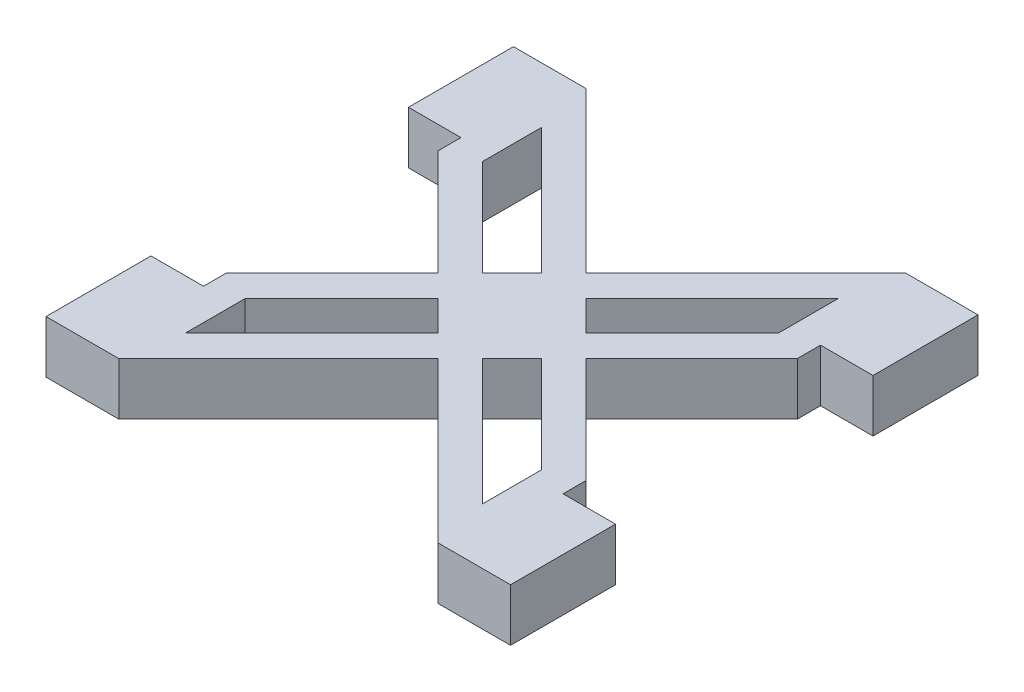
SolidWorks part; units mm, degrees
ref_plane "Front Plane" through (0, 0, 0) normal (0, 0, 1) x (1, 0, 0)
ref_plane "Top Plane" through (0, 0, 0) normal (0, 1, 0) x (1, 0, 0)
ref_plane "Right Plane" through (0, 0, 0) normal (1, 0, 0) x (0, 0, -1)
sketch "Sketch1" plane through (0, 0, 0) normal (0, 1, 0) x (1, 0, 0)
  line L0 (8.9803, 0) -> (-8.9803, 0) construction
  line L1 (6.2862, 2.6941) -> (2.6941, 6.2862)
  line L2 (4.4901, 4.4901) -> (-20.373, 29.3533) construction
  line L3 (-28.0924, 15.5702) -> (-28.0924, 28.2702)
  line L4 (0, 0) -> (24.8632, 24.8632) construction
  line L5 (21.7424, 15.5702) -> (21.7424, 12.7621)
  line L6 (28.0924, 28.2702) -> (19.2899, 28.2702)
  line L7 (0, 0) -> (-24.8632, 24.8632) construction
  line L8 (28.0924, 15.5702) -> (21.7424, 15.5702)
  line L9 (-8.9803, 0) -> (-21.7424, 12.7621)
  line L10 (2.6941, -6.2862) -> (6.2862, -2.6941)
  line L11 (-4.4901, -4.4901) -> (-29.3533, 20.373) construction
  line L12 (28.0924, 15.5702) -> (28.0924, 28.2702)
  line L13 (-6.2862, 2.6941) -> (-2.6941, 6.2862)
  line L14 (0, -27.6063) -> (0, 27.6063) construction
  line L15 (0, 0) -> (-24.8632, -24.8632) construction
  line L16 (0, 0) -> (24.8632, -24.8632) construction
  line L17 (-21.7424, -15.5702) -> (-21.7424, -12.7621)
  line L18 (-28.0924, -28.2702) -> (-19.2899, -28.2702)
  line L19 (-28.0924, -15.5702) -> (-21.7424, -15.5702)
  line L20 (-6.2862, -2.6941) -> (-2.6941, -6.2862)
  line L21 (28.0924, -15.5702) -> (28.0924, -28.2702)
  line L22 (8.9803, 0) -> (21.7424, -12.7621)
  line L23 (-8.9803, 0) -> (-21.7424, -12.7621)
  line L24 (28.0924, -15.5702) -> (21.7424, -15.5702)
  line L25 (28.0924, -28.2702) -> (19.2899, -28.2702)
  line L26 (21.7424, -15.5702) -> (21.7424, -12.7621)
  line L27 (-28.0924, -15.5702) -> (-28.0924, -28.2702)
  line L28 (0, -8.9803) -> (-19.2899, -28.2702)
  line L29 (-28.0924, 15.5702) -> (-21.7424, 15.5702)
  line L30 (-28.0924, 28.2702) -> (-19.2899, 28.2702)
  line L31 (-21.7424, 15.5702) -> (-21.7424, 12.7621)
  line L32 (6.2862, 2.6941) -> (17.9324, 14.3403)
  line L33 (17.9324, -19.3802) -> (17.9324, -14.3403) construction
  line L34 (0, -3.5921) -> (20.8681, -24.4602) construction
  line L35 (-17.9324, -21.5245) -> (-17.9324, -14.3403)
  line L36 (0, -3.5921) -> (-20.8681, -24.4602) construction
  line L37 (2.6941, 6.2862) -> (17.9324, 21.5245)
  line L38 (-2.6941, 6.2862) -> (-17.9324, 21.5245)
  line L39 (17.9324, 21.5245) -> (17.9324, 14.3403)
  line L40 (-17.9324, 21.5245) -> (-17.9324, 14.3403)
  line L41 (0, 3.5921) -> (-20.8681, 24.4602) construction
  line L42 (0, 3.5921) -> (20.8681, 24.4602) construction
  line L43 (-6.2862, 2.6941) -> (-17.9324, 14.3403)
  line L44 (-6.2862, -2.6941) -> (-17.9324, -14.3403)
  line L45 (0, 8.9803) -> (19.2899, 28.2702) construction
  line L46 (-3.5921, 0) -> (-17.9324, 14.3403) construction
  line L47 (0, 8.9803) -> (19.2899, 28.2702)
  line L48 (0, 8.9803) -> (-19.2899, 28.2702) construction
  line L49 (-2.6941, -6.2862) -> (-17.9324, -21.5245)
  line L50 (2.6941, -6.2862) -> (17.9324, -21.5245)
  line L51 (3.5921, 0) -> (17.9324, 14.3403) construction
  line L52 (0, 8.9803) -> (-19.2899, 28.2702)
  line L53 (0, -8.9803) -> (19.2899, -28.2702) construction
  line L54 (17.9324, -21.5245) -> (17.9324, -14.3403)
  line L55 (6.2862, -2.6941) -> (17.9324, -14.3403)
  line L56 (-17.9324, 19.3802) -> (-17.9324, 14.3403) construction
  line L57 (-24.2824, 19.3802) -> (-17.9324, 19.3802) construction
  line L58 (-24.2824, 19.3802) -> (-24.2824, 24.4602) construction
  line L59 (-24.2824, 24.4602) -> (-20.8681, 24.4602) construction
  line L60 (17.9324, 19.3802) -> (17.9324, 14.3403) construction
  line L61 (24.2824, 19.3802) -> (17.9324, 19.3802) construction
  line L62 (24.2824, 19.3802) -> (24.2824, 24.4602) construction
  line L63 (24.2824, 24.4602) -> (20.8681, 24.4602) construction
  line L64 (-24.2824, -19.3802) -> (-17.9324, -19.3802) construction
  line L65 (-24.2824, -19.3802) -> (-24.2824, -24.4602) construction
  line L66 (-17.9324, -19.3802) -> (-17.9324, -14.3403) construction
  line L67 (-24.2824, -24.4602) -> (-20.8681, -24.4602) construction
  line L68 (24.2824, -24.4602) -> (20.8681, -24.4602) construction
  line L69 (24.2824, -19.3802) -> (17.9324, -19.3802) construction
  line L70 (24.2824, -19.3802) -> (24.2824, -24.4602) construction
  line L71 (-3.5921, 0) -> (-17.9324, -14.3403) construction
  line L72 (0, -8.9803) -> (19.2899, -28.2702)
  line L73 (8.9803, 0) -> (21.7424, 12.7621) construction
  line L74 (3.5921, 0) -> (17.9324, -14.3403) construction
  line L75 (8.9803, 0) -> (21.7424, 12.7621)
  point P0 (0, 0)
  dimension "D7" = 6.35
  dimension "D1" = 45
  dimension "D3" = 28.0924
  dimension "D4" = 12.7
  dimension "D5" = 6.35
  dimension "D2" = 6.35
  dimension "D6" = 3.81
extrude "Boss-Extrude1" add sketch "Sketch1" along normal blind 6.35
equation "\"D3@Sketch1\"=2.212/2"
